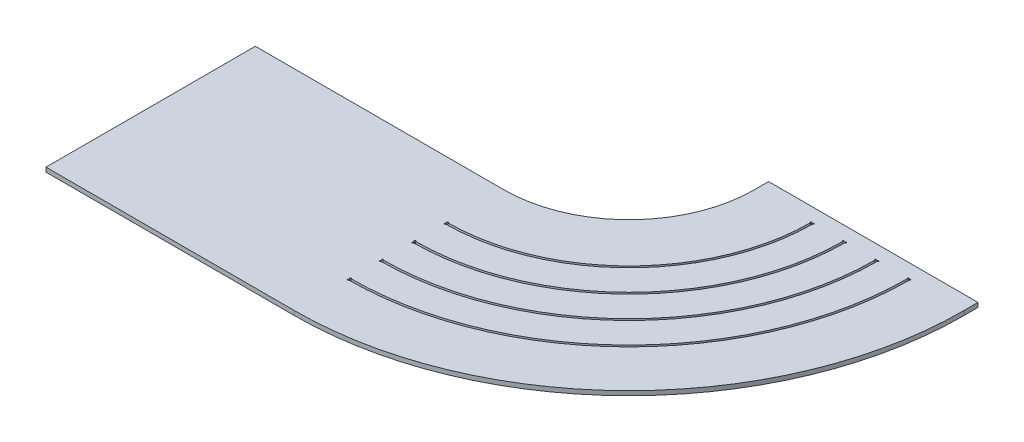
SolidWorks part; units mm, degrees
material "Beech"
ref_plane "Front Plane" through (0, 0, 0) normal (0, 0, 1) x (1, 0, 0)
ref_plane "Top Plane" through (0, 0, 0) normal (0, 1, 0) x (1, 0, 0)
ref_plane "Right Plane" through (0, 0, 0) normal (1, 0, 0) x (0, 0, -1)
sketch "Sketch1" plane through (0, 384.469, 0) normal (0, -1, 0) x (1, 0, 0)
  line L86 (1658.2316, -268.8862) -> (2113.4816, -268.8862)
  line L87 (2113.4816, -268.8862) -> (2113.4816, -237.9362)
  line L88 (1385.8566, 489.6888) -> (845.3816, 489.6888)
  line L89 (845.3816, 489.6888) -> (845.3816, 34.4388)
  line L90 (845.3816, 34.4388) -> (1385.8566, 34.4388)
  line L91 (1658.2316, -237.9362) -> (1658.2316, -268.8862)
  line L92 (1658.2316, -268.8862) -> (2113.4816, -268.8862)
  line L93 (2113.4816, -268.8862) -> (2113.4816, -237.9362)
  line L94 (1385.8566, 489.6888) -> (845.3816, 489.6888)
  line L95 (845.3816, 489.6888) -> (845.3816, 34.4388)
  line L96 (845.3816, 34.4388) -> (1385.8566, 34.4388)
  line L97 (1658.2316, -237.9362) -> (1658.2316, -268.8862)
  line L374 (1782.7316, -237.9362) -> (1784.7316, -237.9362)
  line L375 (1385.8566, 160.9388) -> (1385.8566, 158.9388)
  line L376 (1782.7316, -237.9362) -> (1784.7316, -237.9362)
  line L377 (1385.8566, 160.9388) -> (1385.8566, 158.9388)
  line L378 (1993.4816, -237.9362) -> (1995.4816, -237.9362)
  line L379 (1385.8566, 371.6888) -> (1385.8566, 369.6888)
  line L380 (1993.4816, -237.9362) -> (1995.4816, -237.9362)
  line L381 (1385.8566, 371.6888) -> (1385.8566, 369.6888)
  line L382 (1923.2316, -237.9362) -> (1925.2316, -237.9362)
  line L383 (1385.8566, 301.4388) -> (1385.8566, 299.4388)
  line L384 (1923.2316, -237.9362) -> (1925.2316, -237.9362)
  line L385 (1385.8566, 301.4388) -> (1385.8566, 299.4388)
  line L386 (1852.9816, -237.9362) -> (1854.9816, -237.9362)
  line L387 (1385.8566, 231.1888) -> (1385.8566, 229.1888)
  line L388 (1852.9816, -237.9362) -> (1854.9816, -237.9362)
  line L389 (1385.8566, 231.1888) -> (1385.8566, 229.1888)
  arc A68 (2113.4816, -237.9362) -> (1385.8566, 489.6888) centre (1385.8566, -237.9362) ccw
  arc A69 (1658.2316, -237.9362) -> (1385.8566, 34.4388) centre (1385.8566, -237.9362) ccw
  arc A70 (2113.4816, -237.9362) -> (1385.8566, 489.6888) centre (1385.8566, -237.9362) ccw
  arc A71 (1658.2316, -237.9362) -> (1385.8566, 34.4388) centre (1385.8566, -237.9362) ccw
  arc A276 (1385.8566, 158.9388) -> (1387.3566, 157.436) centre (1385.8566, 157.4388) ccw
  arc A277 (1781.2287, -236.4362) -> (1387.3566, 157.436) centre (1385.8566, -237.9362) ccw
  arc A278 (1781.2287, -236.4362) -> (1782.7316, -237.9362) centre (1781.2316, -237.9362) ccw
  arc A279 (1784.7316, -237.9362) -> (1786.2288, -236.4362) centre (1786.2316, -237.9362) ccw
  arc A280 (1786.2288, -236.4362) -> (1387.3566, 162.436) centre (1385.8566, -237.9362) ccw
  arc A281 (1387.3566, 162.436) -> (1385.8566, 160.9388) centre (1385.8566, 162.4388) ccw
  arc A282 (1385.8566, 158.9388) -> (1387.3566, 157.436) centre (1385.8566, 157.4388) ccw
  arc A283 (1781.2287, -236.4362) -> (1387.3566, 157.436) centre (1385.8566, -237.9362) ccw
  arc A284 (1781.2287, -236.4362) -> (1782.7316, -237.9362) centre (1781.2316, -237.9362) ccw
  arc A285 (1784.7316, -237.9362) -> (1786.2288, -236.4362) centre (1786.2316, -237.9362) ccw
  arc A286 (1786.2288, -236.4362) -> (1387.3566, 162.436) centre (1385.8566, -237.9362) ccw
  arc A287 (1387.3566, 162.436) -> (1385.8566, 160.9388) centre (1385.8566, 162.4388) ccw
  arc A288 (1995.4816, -237.9362) -> (1996.9797, -236.4362) centre (1996.9816, -237.9362) ccw
  arc A289 (1996.9797, -236.4362) -> (1387.3566, 373.187) centre (1385.8566, -237.9362) ccw
  arc A290 (1387.3566, 373.187) -> (1385.8566, 371.6888) centre (1385.8566, 373.1888) ccw
  arc A291 (1385.8566, 369.6888) -> (1387.3566, 368.1869) centre (1385.8566, 368.1888) ccw
  arc A292 (1991.9797, -236.4362) -> (1387.3566, 368.1869) centre (1385.8566, -237.9362) ccw
  arc A293 (1991.9797, -236.4362) -> (1993.4816, -237.9362) centre (1991.9816, -237.9362) ccw
  arc A294 (1995.4816, -237.9362) -> (1996.9797, -236.4362) centre (1996.9816, -237.9362) ccw
  arc A295 (1996.9797, -236.4362) -> (1387.3566, 373.187) centre (1385.8566, -237.9362) ccw
  arc A296 (1387.3566, 373.187) -> (1385.8566, 371.6888) centre (1385.8566, 373.1888) ccw
  arc A297 (1385.8566, 369.6888) -> (1387.3566, 368.1869) centre (1385.8566, 368.1888) ccw
  arc A298 (1991.9797, -236.4362) -> (1387.3566, 368.1869) centre (1385.8566, -237.9362) ccw
  arc A299 (1991.9797, -236.4362) -> (1993.4816, -237.9362) centre (1991.9816, -237.9362) ccw
  arc A300 (1925.2316, -237.9362) -> (1926.7295, -236.4362) centre (1926.7316, -237.9362) ccw
  arc A301 (1926.7295, -236.4362) -> (1387.3566, 302.9367) centre (1385.8566, -237.9362) ccw
  arc A302 (1387.3566, 302.9367) -> (1385.8566, 301.4388) centre (1385.8566, 302.9388) ccw
  arc A303 (1385.8566, 299.4388) -> (1387.3566, 297.9367) centre (1385.8566, 297.9388) ccw
  arc A304 (1921.7295, -236.4362) -> (1387.3566, 297.9367) centre (1385.8566, -237.9362) ccw
  arc A305 (1921.7295, -236.4362) -> (1923.2316, -237.9362) centre (1921.7316, -237.9362) ccw
  arc A306 (1925.2316, -237.9362) -> (1926.7295, -236.4362) centre (1926.7316, -237.9362) ccw
  arc A307 (1926.7295, -236.4362) -> (1387.3566, 302.9367) centre (1385.8566, -237.9362) ccw
  arc A308 (1387.3566, 302.9367) -> (1385.8566, 301.4388) centre (1385.8566, 302.9388) ccw
  arc A309 (1385.8566, 299.4388) -> (1387.3566, 297.9367) centre (1385.8566, 297.9388) ccw
  arc A310 (1921.7295, -236.4362) -> (1387.3566, 297.9367) centre (1385.8566, -237.9362) ccw
  arc A311 (1921.7295, -236.4362) -> (1923.2316, -237.9362) centre (1921.7316, -237.9362) ccw
  arc A312 (1854.9816, -237.9362) -> (1856.4792, -236.4362) centre (1856.4816, -237.9362) ccw
  arc A313 (1856.4792, -236.4362) -> (1387.3566, 232.6864) centre (1385.8566, -237.9362) ccw
  arc A314 (1387.3566, 232.6864) -> (1385.8566, 231.1888) centre (1385.8566, 232.6888) ccw
  arc A315 (1385.8566, 229.1888) -> (1387.3566, 227.6864) centre (1385.8566, 227.6888) ccw
  arc A316 (1851.4792, -236.4362) -> (1387.3566, 227.6864) centre (1385.8566, -237.9362) ccw
  arc A317 (1851.4792, -236.4362) -> (1852.9816, -237.9362) centre (1851.4816, -237.9362) ccw
  arc A318 (1854.9816, -237.9362) -> (1856.4792, -236.4362) centre (1856.4816, -237.9362) ccw
  arc A319 (1856.4792, -236.4362) -> (1387.3566, 232.6864) centre (1385.8566, -237.9362) ccw
  arc A320 (1387.3566, 232.6864) -> (1385.8566, 231.1888) centre (1385.8566, 232.6888) ccw
  arc A321 (1385.8566, 229.1888) -> (1387.3566, 227.6864) centre (1385.8566, 227.6888) ccw
  arc A322 (1851.4792, -236.4362) -> (1387.3566, 227.6864) centre (1385.8566, -237.9362) ccw
  arc A323 (1851.4792, -236.4362) -> (1852.9816, -237.9362) centre (1851.4816, -237.9362) ccw
  dimension "D1" = 0
  dimension "D2" = 0
  dimension "D3" = 0
  dimension "D4" = 0
  dimension "D5" = 0
extrude "Boss-Extrude1" add sketch "Sketch1" along normal blind 9.525
